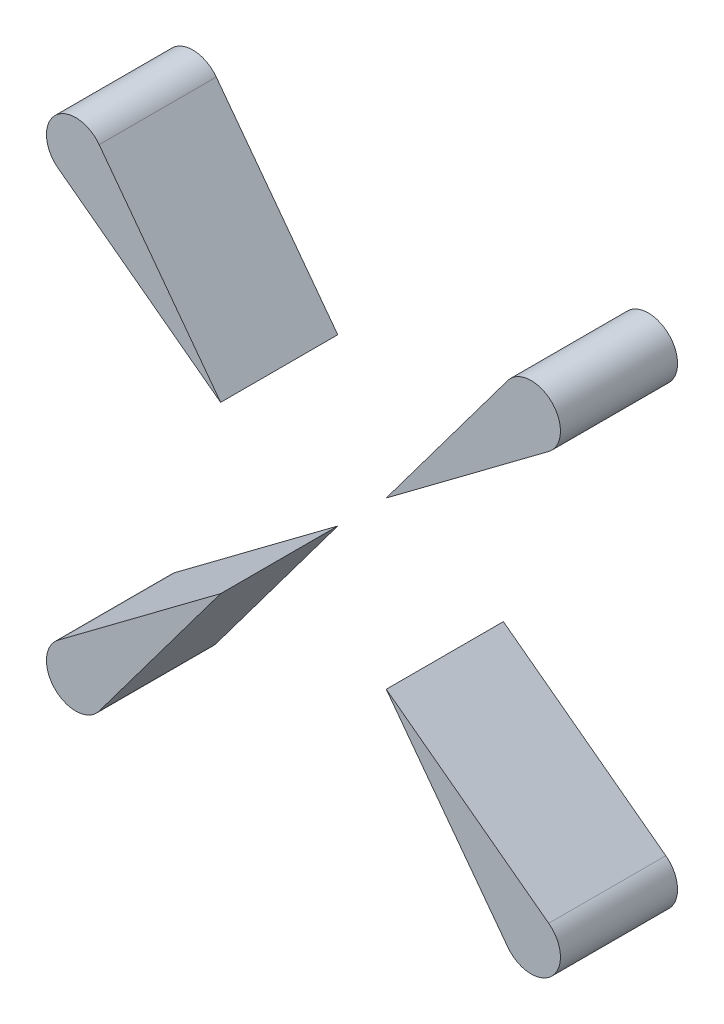
SolidWorks part; units mm, degrees
ref_plane "Front Plane" through (0, 0, 0) normal (0, 0, 1) x (1, 0, 0)
ref_plane "Top Plane" through (0, 0, 0) normal (0, 1, 0) x (1, 0, 0)
ref_plane "Right Plane" through (0, 0, 0) normal (1, 0, 0) x (0, 0, -1)
sketch "Sketch1" plane through (0, 0, 0) normal (0, 0, 1) x (1, 0, 0)
  line L0 (0, 0) -> (0, 18.1779) construction
  line L1 (0, 0) -> (14.0127, 14.0127) construction
  line L4 (0.7071, 0.7071) -> (1.7443, 2.0943)
  line L5 (2.0943, 1.7443) -> (0.7071, 0.7071)
  line L6 (1.7443, -2.0943) -> (0.7071, -0.7071)
  line L7 (0.7071, -0.7071) -> (2.0943, -1.7443)
  line L8 (-2.0943, -1.7443) -> (-0.7071, -0.7071)
  line L9 (-0.7071, -0.7071) -> (-1.7443, -2.0943)
  line L10 (-1.7443, 2.0943) -> (-0.7071, 0.7071)
  line L11 (-0.7071, 0.7071) -> (-2.0943, 1.7443)
  arc A1 (1.7443, 2.0943) -> (2.0943, 1.7443) centre (1.9445, 1.9445) cw
  arc A2 (2.0943, -1.7443) -> (1.7443, -2.0943) centre (1.9445, -1.9445) cw
  arc A3 (-1.7443, -2.0943) -> (-2.0943, -1.7443) centre (-1.9445, -1.9445) cw
  arc A4 (-2.0943, 1.7443) -> (-1.7443, 2.0943) centre (-1.9445, 1.9445) cw
  point P23 (0, 0)
  dimension "D2" = 0.5
  dimension "D3" = 2
  dimension "D1" = 45
  dimension "D4" = 1
  dimension "D5" = 4
extrude "Boss-Extrude1" add sketch "Sketch1" along normal blind 1
sketch "Sketch2" plane through (0, 0, 0) normal (0, 0, 1) x (1, 0, 0)
  line L1 (2.75, -2.75) -> (-2.75, -2.75) construction
  line L2 (2.75, -2.75) -> (2.75, 2.75) construction
  line L3 (2.75, 2.75) -> (-2.75, 2.75) construction
  line L4 (-2.75, -2.75) -> (-2.75, 2.75) construction
  point P0 (0, 0)
  point P6 (0, 0)
  point P7 (-2.75, 0)
  point P8 (0, 2.75)
  dimension "D1" = 5.5
